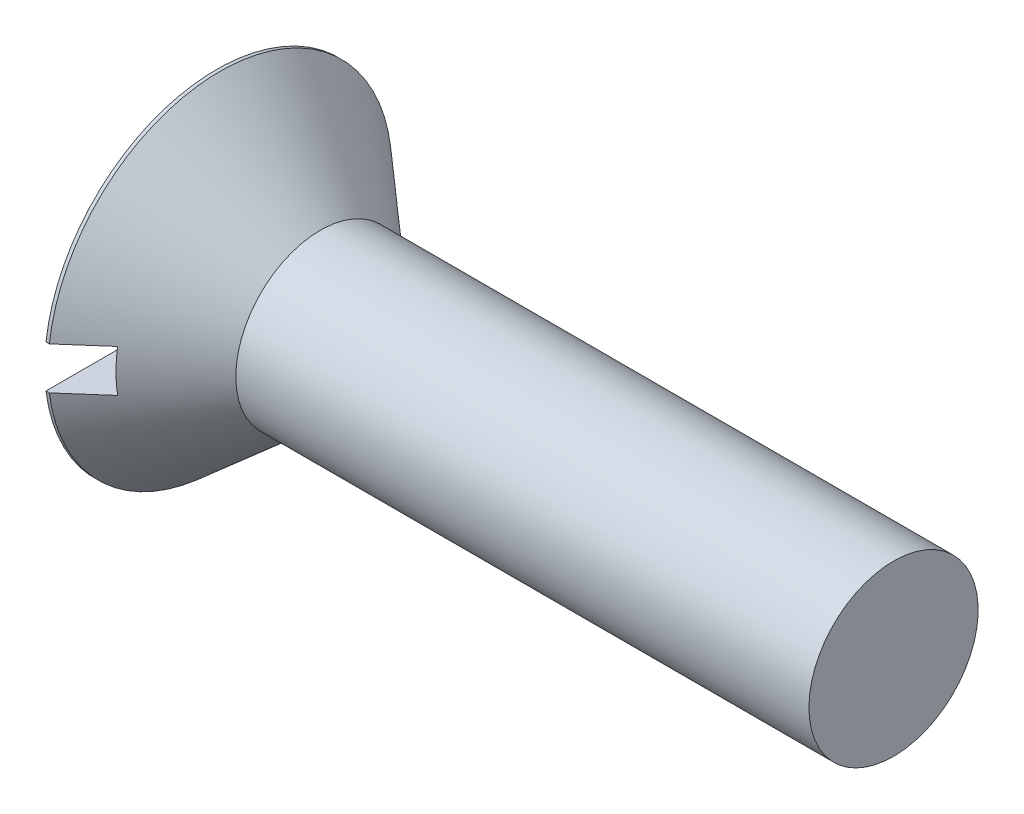
SolidWorks part; units mm, degrees
revolve "Base-Revolve" add sketch "BodySke" angle 360 about L5
sketch "BodySke" plane through (0, 0, 0) normal (0, 0, 1) x (1, 0, 0)
  line L0 (0, 0) -> (0, 9.6774)
  line L1 (0, 9.6774) -> (0.1881, 9.6774)
  line L2 (5.842, 4.7625) -> (38.1, 4.7625)
  line L3 (38.1, 4.7625) -> (38.1, 0)
  line L4 (38.1, 0) -> (0, 0)
  line L5 (-6.35, 0) -> (82.55, 0) construction
  line L6 (5.842, -4.7625) -> (38.1, -4.7625) construction
  line L7 (0.1881, -9.6774) -> (5.842, -4.7625) construction
  line L8 (0.1881, 9.6774) -> (5.842, 4.7625)
  line L9 (0, -9.6774) -> (0.1881, -9.6774) construction
  line L10 (7.4295, 6.35) -> (7.4295, -3.175) construction
  line L11 (6.35, 6.35) -> (6.35, -3.175) construction
  dimension "Diameter" = 9.525
  dimension "Length" = 38.1
  dimension "Head_ht" = 5.842
  dimension "Head_dia" = 19.3548
  dimension "Head_ang" = 82
  dimension "D6" = 0.1881
  dimension "Advance" = 1.5875
  dimension "Thread_nom" = 31.75
cosmetic thread "ThreadCosmetic" [suppressed] parameters "Thread_length"=30.6705, "Thread_minor"=7.9248
extrude "Slot" cut sketch "Sketch2" against normal blind 2.2352
sketch "Sketch2" plane through (0, 0, 0) normal (-1, 0, 0) x (0, 0, 1)
  line L0 (-9.6774, -1.1938) -> (9.6774, -1.1938)
  line L1 (-9.6774, -1.1938) -> (-9.6774, 1.1938)
  line L2 (9.6774, 1.1938) -> (-9.6774, 1.1938)
  line L3 (9.6774, 1.1938) -> (9.6774, -1.1938)
  dimension "Slot_width" = 2.3876
  dimension "D1" = 1.1938
  dimension "D2" = 19.3548
  dimension "D3" = 9.6774
ref_plane "Plane1" through (0, 0, 0) normal (0, 0, 1) x (1, 0, 0)
ref_plane "Plane2" through (0, 0, 0) normal (0, 1, 0) x (1, 0, 0)
ref_plane "Plane3" through (0, 0, 0) normal (1, 0, 0) x (0, 0, -1)
sketch "Sketch3" plane through (0, 0, 0) normal (-1, 0, 0) x (0, 0, 1)
  line L0 (-1.0922, 6.6421) -> (1.0922, 6.6421)
  line L1 (1.0922, 6.6421) -> (1.0922, -6.6421)
  line L2 (1.0922, -6.6421) -> (-1.0922, -6.6421)
  line L3 (-1.0922, -6.6421) -> (-1.0922, 6.6421)
  dimension "Cross_dia" = 13.2842
  dimension "Cross_width" = 2.1844
  dimension "D1" = 6.6421
  dimension "D2" = 1.0922
ref_plane "Plane4" through (7.9756, 0, 0) normal (-1, 0, 0) x (0, 0, 1)
sketch "Sketch4" plane through (7.9756, 0, 0) normal (-1, 0, 0) x (0, 0, 1)
  line L0 (-0.5461, 0.5461) -> (0.5461, 0.5461)
  line L3 (0.5461, 0.5461) -> (0.5461, -0.5461)
  line L4 (0.5461, -0.5461) -> (-0.5461, -0.5461)
  line L5 (-0.5461, -0.5461) -> (-0.5461, 0.5461)
  dimension "D2" = 1.0922
  dimension "D1" = 1.0922
  dimension "D3" = 0.5461
  dimension "D4" = 0.5461
loft "Cross" cut profiles "Sketch3", "Sketch4"
pattern_circular "CirPattern1" count 2 every 90 about axis through (0, 0, 0) along (1, 0, 0) of "Cross"
sketch "ThdSchSke" plane through (0, 0, 0) normal (0, 0, 1) x (1, 0, 0)
  line L0 (7.4295, -3.9624) -> (6.8693, -4.7625)
  line L1 (7.4295, -3.9624) -> (7.9898, -4.7625)
  line L2 (7.9898, -4.7625) -> (7.9898, -5.9531)
  line L3 (-3.175, 0) -> (5.1513, 0) construction
  line L5 (7.9898, -5.9531) -> (6.8693, -5.9531)
  line L6 (6.8693, -5.9531) -> (6.8693, -4.7625)
  line L7 (0, 9.6774) -> (0, 1.1938) construction
  dimension "Diameter" = 9.525
  dimension "Thread_minor" = 7.9248
  dimension "Start" = 7.4295
revolve "ThreadSchematic" [suppressed] cut sketch "ThdSchSke" angle 360 about L3
pattern_linear "ThdSchPat" [suppressed]
equation "\"D1@Sketch3\" = \"Cross_dia@Sketch3\" / 2"
equation "\"D2@Sketch3\" = \"Cross_width@Sketch3\" / 2"
equation "\"D1@Sketch4\" = \"Cross_width@Sketch3\" *.5"
equation "\"D2@Sketch4\" = \"D1@Sketch4\""
equation "\"D4@Sketch4\" = \"D2@Sketch4\" / 2"
equation "\"D3@Sketch4\" = \"D1@Sketch4\" / 2"
equation "\"D1@Sketch2\" = \"Slot_width@Sketch2\" / 2"
equation "\"D2@Sketch2\" = \"Head_dia@BodySke\""
equation "\"D3@Sketch2\" = \"D2@Sketch2\" / 2"
equation "\"Thread_length@ThreadCosmetic\" = ((sgn( (\"Length@BodySke\" - \"Advance@BodySke\" - \"Head_ht@BodySke\" ) - \"Thread_nom@BodySke\" )-1)*( (\"Length@BodySke\" - \"Advance@BodySke\" - \"Head_ht@BodySke\" ) - \"Thread_nom@BodySke\" ))/-2+ \"Thread_nom@BodySke\""
equation "\"Thread_minor@ThdSchSke\" = \"Thread_minor@ThreadCosmetic\""
equation "\"Diameter@ThdSchSke\" = \"Diameter@BodySke\""
equation "\"Overcut@ThdSchSke\" = \"Diameter@BodySke\" * 1.25"
equation "\"Start@ThdSchSke\" = 0.000001 + \"Length@BodySke\" - \"Thread_length@ThreadCosmetic\"  '---Countersunk---"
equation "\"Num_threads@ThdSchPat\" = int( \"Thread_length@ThreadCosmetic\" / \"Advance@BodySke\" + 0.999 )  + 1"
equation "\"Advance@ThdSchPat\" = \"Thread_length@ThreadCosmetic\" /  (\"Num_threads@ThdSchPat\" - 1) 'relax it"
